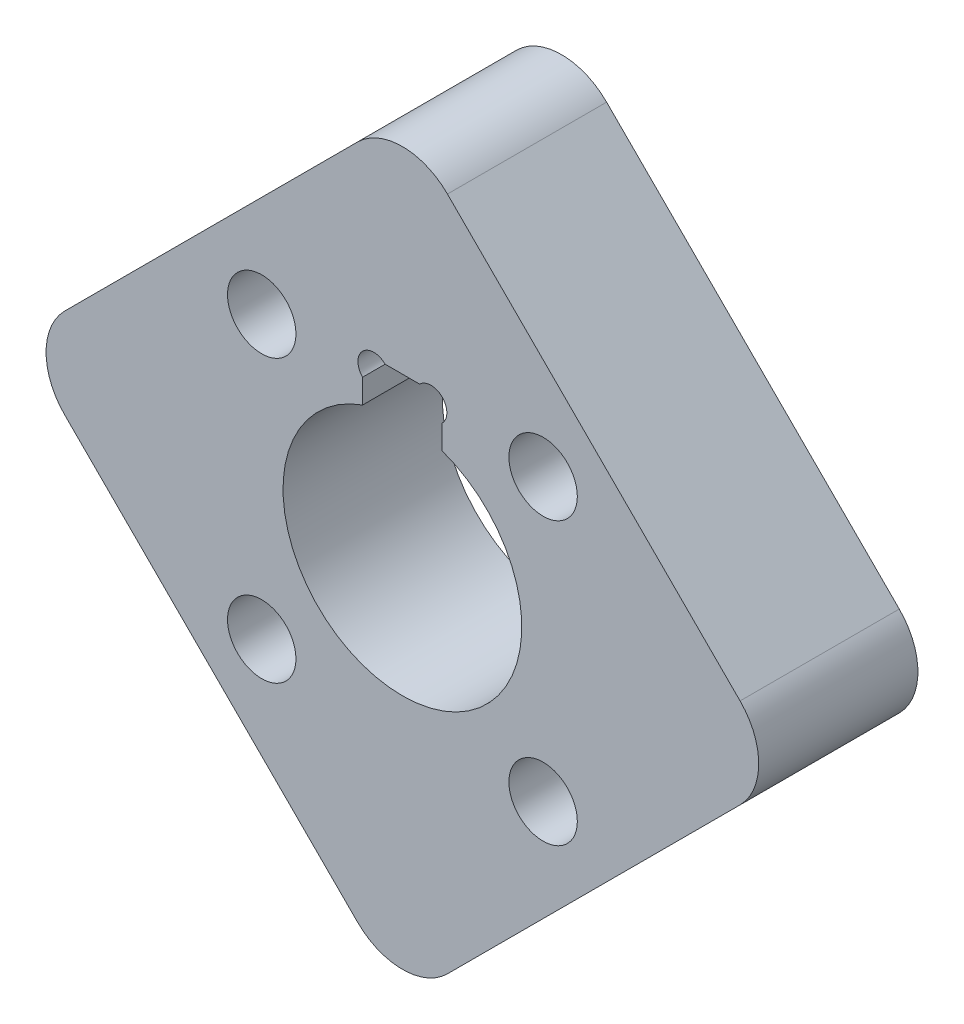
SolidWorks part; units mm, degrees
material "3.1325 (EN-AW 2017A)"
ref_plane "正面" through (0, 0, 0) normal (0, 0, 1) x (1, 0, 0)
ref_plane "平面" through (0, 0, 0) normal (0, 1, 0) x (1, 0, 0)
ref_plane "右側面" through (0, 0, 0) normal (1, 0, 0) x (0, 0, -1)
sketch "ｽｹｯﾁ1" plane through (0, 0, 0) normal (0, 0, 1) x (1, 0, 0)
  line L0 (-21.2132, -2.8284) -> (-2.8284, -21.2132)
  line L1 (-21.2132, 2.8284) -> (-2.8284, 21.2132)
  line L2 (2.8284, -21.2132) -> (21.2132, -2.8284)
  line L3 (2.8284, 21.2132) -> (21.2132, 2.8284)
  line L4 (0, 0) -> (0, 24.0416) construction
  line L5 (0, 0) -> (24.0416, 0) construction
  line L6 (0, 0) -> (12.0208, 12.0208) construction
  line L7 (-2.5, 8.5858) -> (-2.5, 7.0711)
  line L8 (-2.5, 10) -> (2.5, 10) construction
  line L9 (-2.5, 8.5858) -> (-2.5, 5) construction
  line L10 (-2.5, 5) -> (2.5, 5) construction
  line L11 (2.5, 8.5858) -> (2.5, 5) construction
  line L12 (-1.0858, 10) -> (1.0858, 10)
  line L13 (2.5, 8.5858) -> (2.5, 7.0711)
  line L14 (1.7929, 9.2929) -> (2.5, 10) construction
  arc A0 (-21.2132, 2.8284) -> (-21.2132, -2.8284) centre (-18.3848, 0) ccw
  arc A1 (-2.8284, -21.2132) -> (2.8284, -21.2132) centre (0, -18.3848) ccw
  arc A2 (21.2132, -2.8284) -> (21.2132, 2.8284) centre (18.3848, 0) ccw
  arc A3 (-2.8284, 21.2132) -> (2.8284, 21.2132) centre (0, 18.3848) cw
  arc A4 (-2.5, 7.0711) -> (2.5, 7.0711) centre (0, 0) ccw
  arc A5 (-2.5, 8.5858) -> (-1.0858, 10) centre (-1.7929, 9.2929) cw
  circle A6 centre (0, 0) radius 8.5
  arc A7 (2.5, 8.5858) -> (1.0858, 10) centre (1.7929, 9.2929) ccw
  point P16 (8.8388, 8.8388)
  point P23 (0, 10)
  point P29 (0, 10)
  point P32 (8.8388, -8.8388)
  point P33 (-8.8388, -8.8388)
  point P34 (-8.8388, 8.8388)
  point P35 (0, 0)
  dimension "D1" = 4
  dimension "D4" = 15
  dimension "D9" = 17
  dimension "D7" = 2
  dimension "D2" = 34
  dimension "D3" = 12.5
  dimension "D5" = 5
  dimension "D6" = 2.5
  dimension "D10" = 5
  dimension "D11" = 45
  dimension "D8" = 4
extrude "ﾎﾞｽ - 押し出し1" add sketch "ｽｹｯﾁ1" along normal blind 10 contours A3 L1 A0 L0 A1 L2 A2 L3 A7 L13 A6 L7 A5 L12 | L7 A6 L13 A4
hole_wizard "M4 すきま穴1" positions "3Dｽｹｯﾁ2" profile "ｽｹｯﾁ2" hole size "M4" standard "JIS" end condition through all
sketch3d "3Dｽｹｯﾁ2"
  point P19 (-8.8388, 8.8388, 10)
  point P21 (8.8388, 8.8388, 10)
  point P23 (8.8388, -8.8388, 10)
  point P25 (-8.8388, -8.8388, 10)
sketch "ｽｹｯﾁ2" plane through (-8.8388, 8.8388, 10) normal (1, 0, 0) x (0, -1, 0)
  line L0 (0, 0) -> (0, 10)
  line L1 (0, 10) -> (2.15, 10)
  line L2 (2.15, 10) -> (2.15, 0)
  line L5 (2.15, 0) -> (0, 0)
  line L11 (0, -6.35) -> (0, 107.95) construction
  dimension "通し穴の直径" = 4.3
  dimension "通し穴の深さ" = 10
hole_wizard "M4 丸皿ねじ用皿穴1" [suppressed] positions "3Dｽｹｯﾁ4" profile "ｽｹｯﾁ4" countersink size "M4" standard "JIS"
sketch3d "3Dｽｹｯﾁ4"
  point P0 (-8.8388, 8.8388, 10)
  point P2 (8.8388, 8.8388, 10)
  point P4 (8.8388, -8.8388, 10)
  point P6 (-8.8388, -8.8388, 10)
sketch "ｽｹｯﾁ4" plane through (-8.8388, 8.8388, 10) normal (1, 0, 0) x (0, -1, 0)
  line L0 (0, 0) -> (0, 10)
  line L1 (0, 10) -> (2.15, 10)
  line L2 (2.15, 10) -> (2.15, 2.55)
  line L3 (2.15, 2.55) -> (4.7, 0)
  line L5 (4.7, 0) -> (0, 0)
  line L6 (-2.15, 2.55) -> (-4.7, 0) construction
  line L11 (0, -6.35) -> (0, 107.95) construction
  dimension "通し穴の直径" = 4.3
  dimension "通し穴の深さ" = 10
  dimension "表面の皿穴の直径" = 9.4
  dimension "表面の皿穴の角度" = 90
sketch "ｽｹｯﾁ5" [suppressed] plane through (0, 0, 0) normal (0, 0, -1) x (-1, 0, 0)
  line L8 (-5.6569, 24.0416) -> (-24.0416, 5.6569)
  line L9 (-24.0416, -5.6569) -> (-5.6569, -24.0416)
  line L10 (5.6569, -24.0416) -> (24.0416, -5.6569)
  line L11 (24.0416, 5.6569) -> (5.6569, 24.0416)
  line L12 (-5.6569, 24.0416) -> (-24.0416, 5.6569)
  line L13 (-24.0416, -5.6569) -> (-5.6569, -24.0416)
  line L14 (5.6569, -24.0416) -> (24.0416, -5.6569)
  line L15 (24.0416, 5.6569) -> (5.6569, 24.0416)
  arc A8 (5.6569, 24.0416) -> (-5.6569, 24.0416) centre (0, 18.3848) ccw
  arc A9 (-24.0416, 5.6569) -> (-24.0416, -5.6569) centre (-18.3848, 0) ccw
  arc A10 (-5.6569, -24.0416) -> (5.6569, -24.0416) centre (0, -18.3848) ccw
  arc A11 (24.0416, -5.6569) -> (24.0416, 5.6569) centre (18.3848, 0) ccw
  arc A12 (5.6569, 24.0416) -> (-5.6569, 24.0416) centre (0, 18.3848) ccw
  arc A13 (-24.0416, 5.6569) -> (-24.0416, -5.6569) centre (-18.3848, 0) ccw
  arc A14 (-5.6569, -24.0416) -> (5.6569, -24.0416) centre (0, -18.3848) ccw
  arc A15 (24.0416, -5.6569) -> (24.0416, 5.6569) centre (18.3848, 0) ccw
  dimension "D1" = 4
equation "\"ミル径\"= 1"
equation "\"コーナR面取り小\"= 2"
equation "\"コーナR面取り大\"= 5"
equation "\"D7@ｽｹｯﾁ1\"=2"
